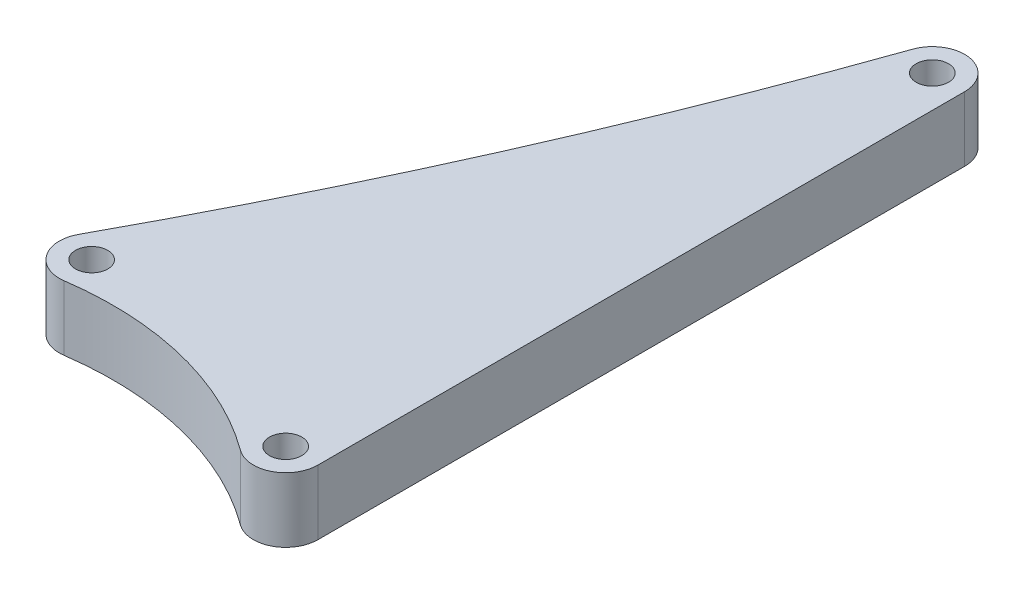
SolidWorks part; units mm, degrees
ref_plane "Front Plane" through (0, 0, 0) normal (0, 0, 1) x (1, 0, 0)
ref_plane "Top Plane" through (0, 0, 0) normal (0, 1, 0) x (1, 0, 0)
ref_plane "Right Plane" through (0, 0, 0) normal (1, 0, 0) x (0, 0, -1)
sketch "Sketch1" plane through (0, 0, 0) normal (0, 1, 0) x (1, 0, 0)
  line L0 (0, 0) -> (0, -5) construction
  line L1 (0, 0) -> (20, 0) construction
  line L2 (20, 0) -> (20, -10) construction
  line L3 (20, 0) -> (20, 40) construction
  line L4 (22.5, 40) -> (22.5, -10)
  circle A0 centre (0, -5) radius 2.5
  circle A1 centre (20, -10) radius 2.5
  circle A2 centre (20, 40) radius 2.5
  arc A3 (0.3545, -7.4747) -> (18.5227, -12.0168) centre (3.87, -32.0198) cw
  arc A4 (17.6413, 40.8287) -> (-2.1957, -3.8045) centre (-269.3905, 141.6736) cw
  circle A5 centre (20, 40) radius 1.25
  circle A6 centre (0, -5) radius 1.25
  circle A7 centre (20, -10) radius 1.25
  dimension "D1" = 5
  dimension "D2" = 5
  dimension "D5" = 5
  dimension "D10" = 2.5
  dimension "D3" = 10
  dimension "D4" = 20
  dimension "D6" = 40
  dimension "D7" = 5
extrude "Boss-Extrude1" add sketch "Sketch1" along normal blind 5 contours A0 A6 | A2 A4 A0 A3 A1 L4 | A1 A7 | A2 A5
